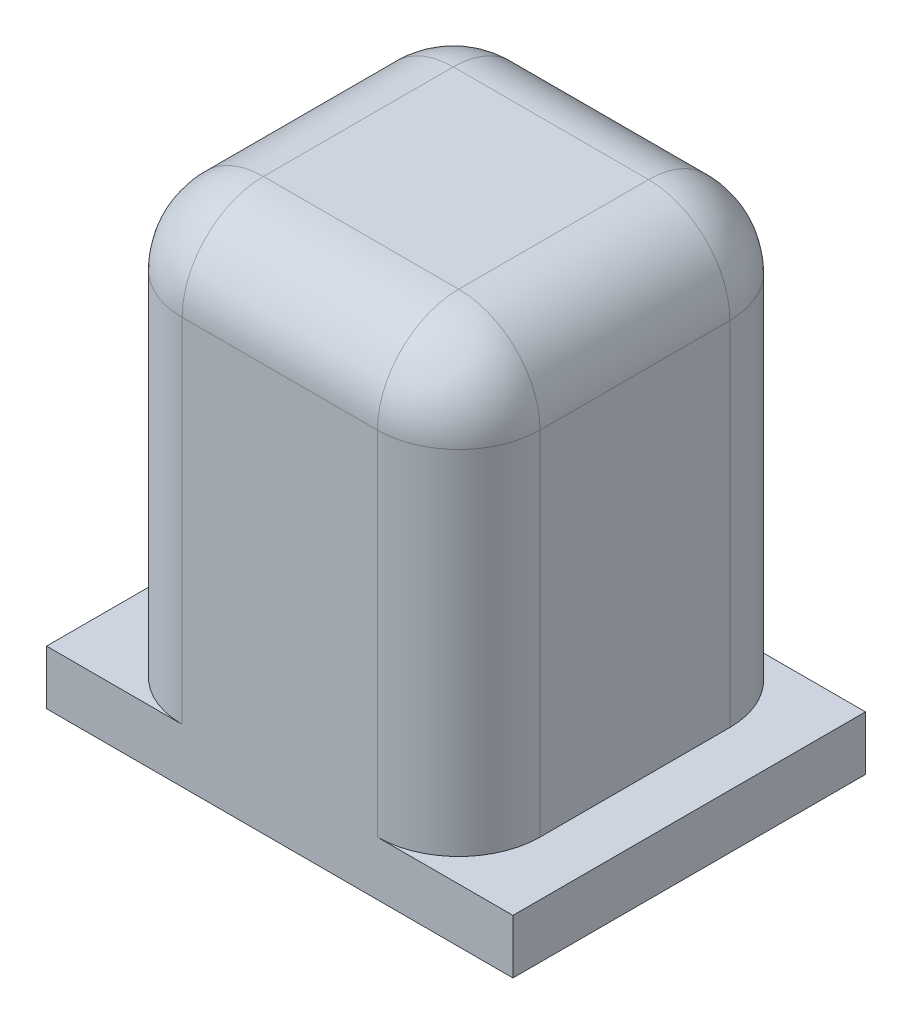
SolidWorks part; units mm, degrees
ref_plane "Front Plane" through (0, 0, 0) normal (0, 0, 1) x (1, 0, 0)
ref_plane "Top Plane" through (0, 0, 0) normal (0, 1, 0) x (1, 0, 0)
ref_plane "Right Plane" through (0, 0, 0) normal (1, 0, 0) x (0, 0, -1)
sketch "Sketch2" plane through (0, 0, 0) normal (0, 0, 1) x (1, 0, 0)
  line L0 (32.25, 51.25) -> (32.25, 53.25) construction
  line L1 (32.45, 56.5) -> (39.05, 56.5)
  line L2 (32.45, 56.5) -> (32.45, 47.5)
  line L3 (32.45, 47.5) -> (39.05, 47.5)
  line L4 (39.05, 56.5) -> (39.05, 47.5)
  line L5 (39.25, 51.25) -> (39.25, 53.25) construction
  line L7 (37.5, 46.5) -> (34, 46.5) construction
  line L8 (35.75, 56.5) -> (35.75, 47.5) construction
  line L9 (39.05, 47.5) -> (40.05, 47.5)
  line L10 (39.05, 47.5) -> (39.05, 48.5)
  line L11 (39.05, 48.5) -> (40.05, 48.5)
  line L12 (40.05, 47.5) -> (40.05, 48.5)
  line L13 (32.45, 47.5) -> (31.45, 47.5)
  line L14 (31.45, 47.5) -> (31.45, 48.5)
  line L15 (32.45, 48.5) -> (31.45, 48.5)
  line L16 (32.45, 48.5) -> (32.45, 47.5)
  point P15 (39.55, 47.5)
  point P16 (31.95, 47.5)
  dimension "D1" = 0.2
  dimension "D2" = 0.2
  dimension "D3" = 9
  dimension "D4" = 1
  dimension "D5" = 1
  dimension "D6" = 1
extrude "Boss-Extrude1" add sketch "Sketch2" along normal blind 6.5 contours L2 L15 L14 L13 | L8 L1 L2 L3 | L1 L8 L3 L4 | L9 L12 L11 L4
fillet "Fillet1" radius 1.5 8 edges at (39.05, 52.5, 0) (39.05, 52.5, 6.5) (32.45, 52.5, 0) (32.45, 52.5, 6.5) (39.05, 56.5, 3.25) (32.45, 56.5, 3.25) (35.75, 56.5, 0) (35.75, 56.5, 6.5)
